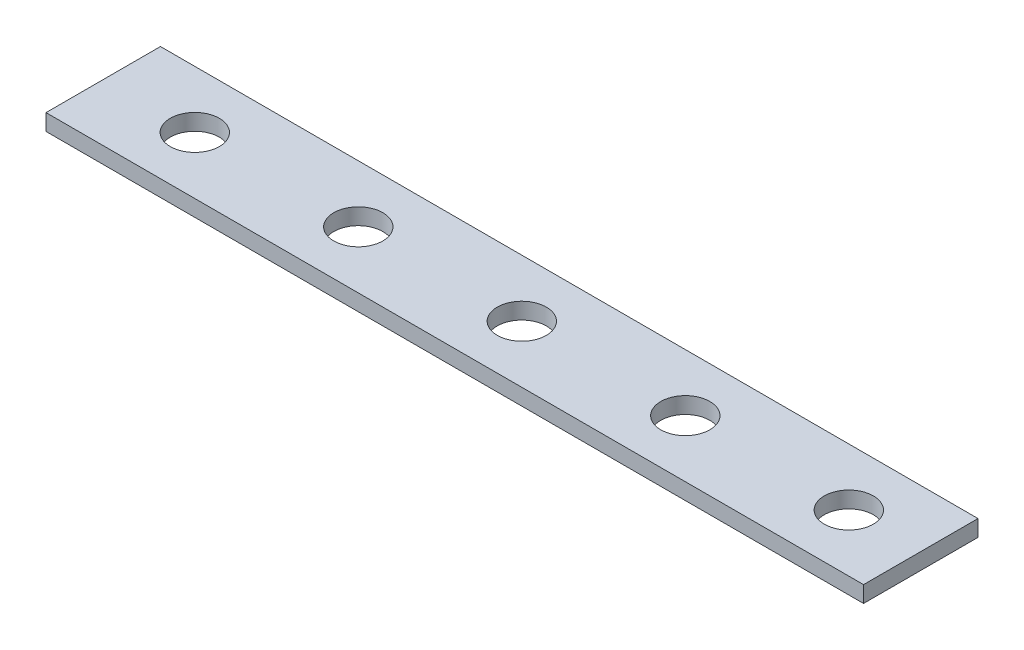
SolidWorks part; units mm, degrees
ref_plane "Front Plane" through (0, 0, 0) normal (0, 0, 1) x (1, 0, 0)
ref_plane "Top Plane" through (0, 0, 0) normal (0, 1, 0) x (1, 0, 0)
ref_plane "Right Plane" through (0, 0, 0) normal (1, 0, 0) x (0, 0, -1)
sketch "Sketch1" plane through (0, 0, 0) normal (0, 1, 0) x (1, 0, 0)
  line L1 (-33.6, 18.3167) -> (16.4, 18.3167)
  line L2 (-33.6, 18.3167) -> (-33.6, 11.3167)
  line L3 (-33.6, 11.3167) -> (16.4, 11.3167)
  line L4 (16.4, 18.3167) -> (16.4, 11.3167)
  dimension "D1" = 7
  dimension "D2" = 50
extrude "Boss-Extrude1" add sketch "Sketch1" along normal blind 1
sketch "Sketch2" plane through (0, 1, 0) normal (0, 1, 0) x (1, 0, 0)
  line L0 (-33.6, 14.8167) -> (16.4, 14.8167) construction
  line L1 (-33.6, 18.3167) -> (-33.6, 11.3167) construction
  line L2 (16.4, 11.3167) -> (16.4, 18.3167) construction
  circle A0 centre (-28.0002, 14.8167) radius 1.5
extrude "Cut-Extrude1" cut sketch "Sketch2" against normal through all contours A0
sketch "Sketch3" plane through (0, 1, 0) normal (0, 1, 0) x (1, 0, 0)
  line L0 (-33.6, 14.8167) -> (16.4, 14.8167) construction
  line L1 (-33.6, 18.3167) -> (-33.6, 11.3167) construction
  line L2 (16.4, 11.3167) -> (16.4, 18.3167) construction
pattern_linear "LPattern2" count 5 spacing 10 along (1, 0, 0) of "Cut-Extrude1"
